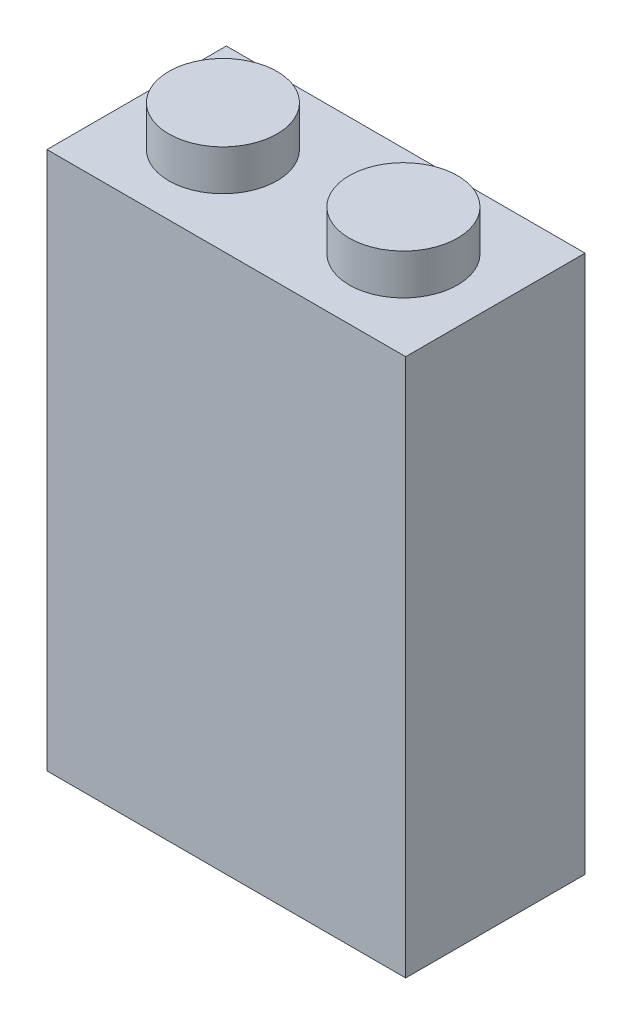
SolidWorks part; units mm, degrees
ref_plane "Front Plane" through (0, 0, 0) normal (0, 0, 1) x (1, 0, 0)
ref_plane "Top Plane" through (0, 0, 0) normal (0, 1, 0) x (1, 0, 0)
ref_plane "Right Plane" through (0, 0, 0) normal (1, 0, 0) x (0, 0, -1)
sketch "Sketch1" plane through (0, 0, 0) normal (0, 0, 1) x (1, 0, 0)
  line L1 (-7.95, -11.925) -> (7.95, -11.925)
  line L2 (-7.95, -11.925) -> (-7.95, 11.925)
  line L3 (-7.95, 11.925) -> (7.95, 11.925)
  line L4 (7.95, -11.925) -> (7.95, 11.925)
  line L5 (-7.95, -11.925) -> (7.95, 11.925) construction
  line L6 (-7.95, 11.925) -> (7.95, -11.925) construction
  point P0 (0, 0)
  dimension "D1" = 23.85
  dimension "D2" = 15.9
extrude "Boss-Extrude1" add sketch "Sketch1" against normal blind 7.95
sketch "Sketch2" plane through (0, 11.925, 0) normal (0, 1, 0) x (1, 0, 0)
  line L0 (7.95, 0) -> (-7.95, 0) construction
  line L1 (-7.95, 7.95) -> (-7.95, 0) construction
  circle A0 centre (-4.05, 3.9) radius 2.4
  dimension "D1" = 4.8
  dimension "D2" = 3.9
  dimension "D3" = 3.9
extrude "Boss-Extrude2" add sketch "Sketch2" along normal blind 1.8
pattern_linear "LPattern1" count 2 spacing 8 along (1, 0, 0) of "Boss-Extrude2"
shell "Shell1" thickness 1.2
